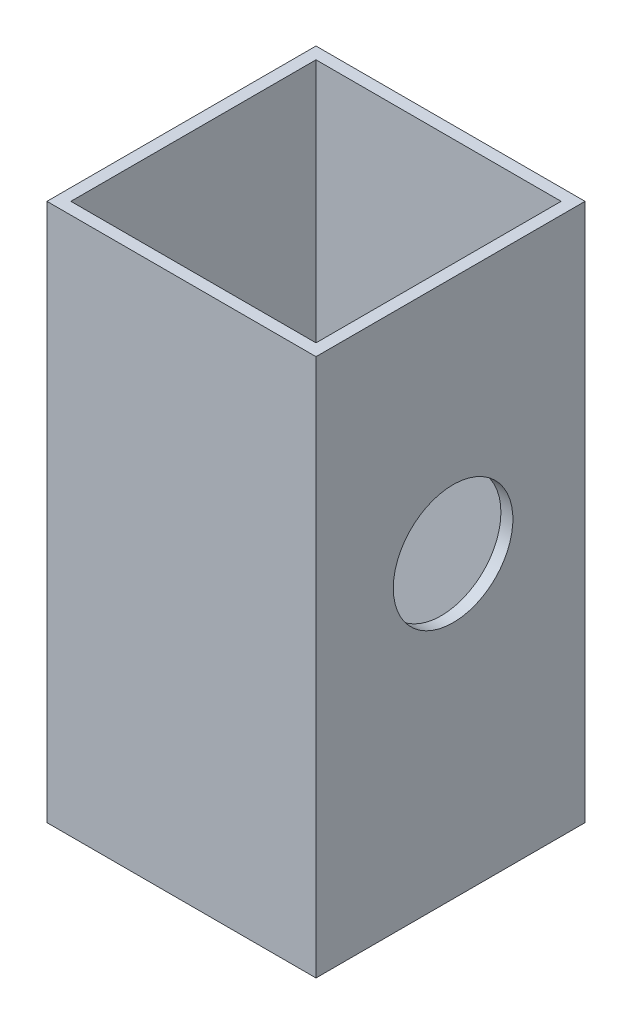
SolidWorks part; units mm, degrees
ref_plane "前视基准面" through (0, 0, 0) normal (0, 0, 1) x (1, 0, 0)
ref_plane "上视基准面" through (0, 0, 0) normal (0, 1, 0) x (1, 0, 0)
ref_plane "右视基准面" through (0, 0, 0) normal (1, 0, 0) x (0, 0, -1)
sketch "草图1" plane through (0, 0, 0) normal (0, 1, 0) x (1, 0, 0)
  line L1 (0, 0) -> (-22.5, 0)
  line L2 (0, 0) -> (0, -22.5)
  line L3 (0, -22.5) -> (-22.5, -22.5)
  line L4 (-22.5, 0) -> (-22.5, -22.5)
  dimension "D1" = 22.5
  dimension "D2" = 22.5
extrude "凸台-拉伸1" add sketch "草图1" along normal blind 45
sketch "草图2" plane through (0, 45, 0) normal (0, 1, 0) x (1, 0, 0)
  line L0 (0, 0) -> (-22.5, 0) construction
  line L1 (-21.5, -1) -> (-1, -1)
  line L2 (-21.5, -1) -> (-21.5, -21.5)
  line L3 (-21.5, -21.5) -> (-1, -21.5)
  line L4 (-1, -1) -> (-1, -21.5)
  line L5 (-22.5, -22.5) -> (0, -22.5) construction
  line L6 (0, -22.5) -> (0, 0) construction
  line L7 (-22.5, 0) -> (-22.5, -22.5) construction
  dimension "D1" = 1
  dimension "D2" = 1
  dimension "D3" = 1
  dimension "D4" = 1
extrude "切除-拉伸1" cut sketch "草图2" against normal blind 40
sketch "草图3" plane through (-22.5, 0, 0) normal (-1, 0, 0) x (0, 0, 1)
  line L0 (0, 45) -> (22.5, 45) construction
  circle A0 centre (11.0361, 25) radius 5
  dimension "D1" = 10
  dimension "D2" = 20
extrude "切除-拉伸2" cut sketch "草图3" against normal blind 40
